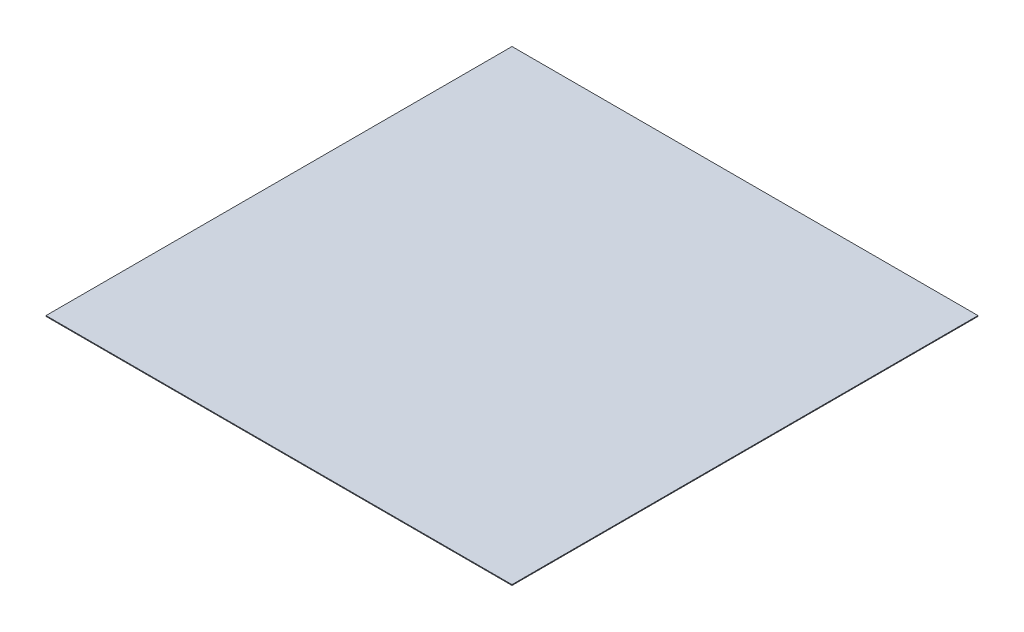
SolidWorks part; units mm, degrees
ref_plane "Front Plane" through (0, 0, 0) normal (0, 0, 1) x (1, 0, 0)
ref_plane "Top Plane" through (0, 0, 0) normal (0, 1, 0) x (1, 0, 0)
ref_plane "Right Plane" through (0, 0, 0) normal (1, 0, 0) x (0, 0, -1)
ref_plane "Plane1"
sketch "Sketch1" plane through (0, 0, 0) normal (0, 1, 0) x (-1, 0, 0)
  line L0 (0, 0) -> (-30480, 0)
  line L1 (-30480, 0) -> (-30480, -30480)
  line L2 (-30480, -30480) -> (0, -30480)
  line L3 (0, -30480) -> (0, 0)
extrude "Extrusion1" add sketch "Sketch1" along normal blind 50.8
